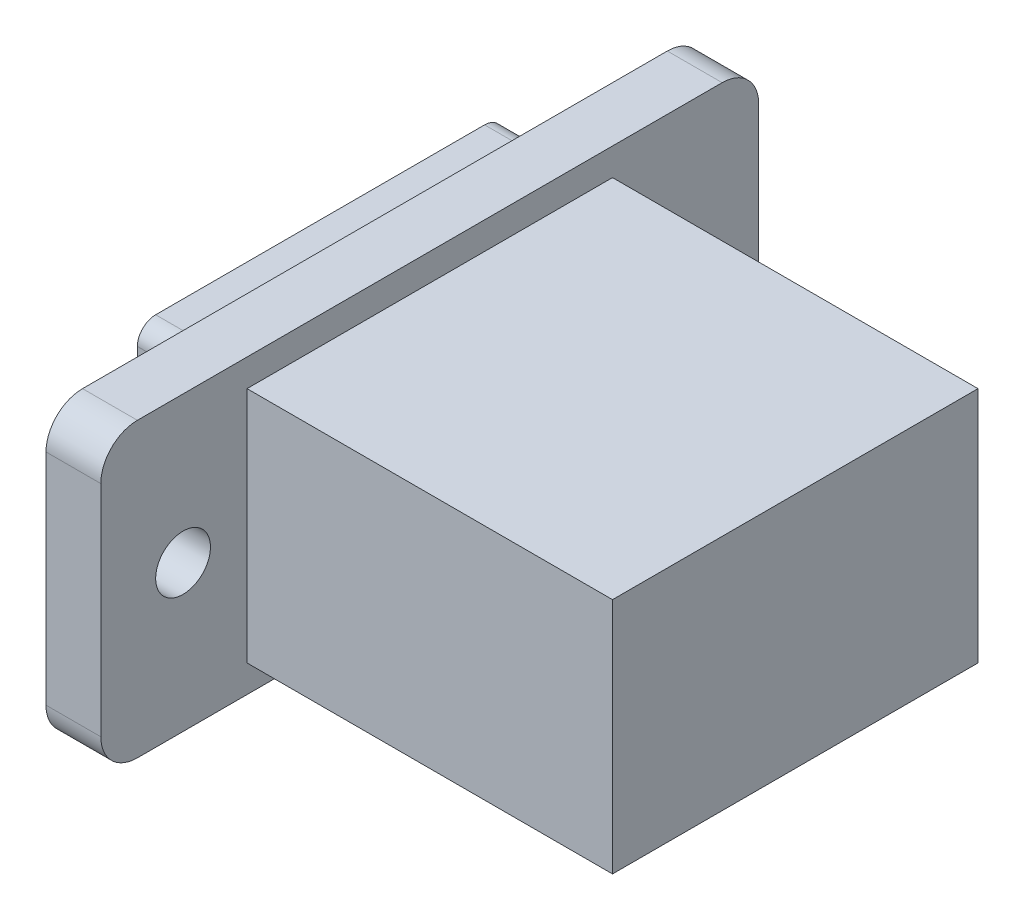
SolidWorks part; units mm, degrees
ref_plane "前视基准面" through (0, 0, 0) normal (0, 0, 1) x (1, 0, 0)
ref_plane "上视基准面" through (0, 0, 0) normal (0, 1, 0) x (1, 0, 0)
ref_plane "右视基准面" through (0, 0, 0) normal (1, 0, 0) x (0, 0, -1)
other "Configuration Table"
sketch "草图1" plane through (0, 0, 0) normal (1, 0, 0) x (0, 0, -1)
  line L1 (0, 0) -> (36, 0)
  line L2 (0, 0) -> (0, 16)
  line L3 (0, 16) -> (36, 16)
  line L4 (36, 0) -> (36, 16)
  dimension "D1" = 16
  dimension "D2" = 36
extrude "凸台-拉伸1" add sketch "草图1" along normal blind 3
sketch "草图2" plane through (0, 0, 0) normal (-1, 0, 0) x (0, 0, 1)
  line L0 (-18, 16) -> (-18, -5.1403) construction
  line L1 (-28, 14.5) -> (-8, 14.5)
  line L2 (-28, 14.5) -> (-28, 1.5)
  line L3 (-28, 1.5) -> (-8, 1.5)
  line L4 (-8, 14.5) -> (-8, 1.5)
  line L5 (-36, 16) -> (0, 16) construction
  line L6 (-36, 8) -> (2.9488, 8) construction
  line L7 (-36, 0) -> (-36, 16) construction
  dimension "D1" = 20
  dimension "D2" = 13
extrude "凸台-拉伸2" add sketch "草图2" along normal blind 3
sketch "草图3" plane through (3, 0, 0) normal (1, 0, 0) x (0, 0, -1)
  line L0 (28, 1.5) -> (8, 1.5) construction
  line L1 (28, 14.5) -> (28, 1.5) construction
  line L2 (8, 14.5) -> (28, 14.5) construction
  line L3 (8, 1.5) -> (8, 14.5) construction
  line L4 (28, 1.5) -> (8, 1.5)
  line L5 (28, 14.5) -> (28, 1.5)
  line L6 (8, 14.5) -> (28, 14.5)
  line L7 (8, 1.5) -> (8, 14.5)
extrude "凸台-拉伸3" add sketch "草图3" along normal blind 20
fillet "圆角1" radius 2 4 edges at (1.5, 0, -36) (1.5, 16, -36) (1.5, 0, 0) (1.5, 16, 0)
fillet "圆角2" radius 1 4 edges at (-1.5, 1.5, -28) (-1.5, 14.5, -28) (-1.5, 1.5, -8) (-1.5, 14.5, -8)
sketch "草图4" plane through (0, 0, 0) normal (-1, 0, 0) x (0, 0, 1)
  line L0 (-36, 8) -> (4.7946, 8) construction
  line L1 (-36, 2) -> (-36, 14) construction
  line L2 (-18, 16) -> (-18, -4.4719) construction
  line L3 (-34, 16) -> (-2, 16) construction
  circle A0 centre (-31.5, 8) radius 1.5
  circle A1 centre (-4.5, 8) radius 1.5
  dimension "D1" = 3
  dimension "D2" = 27
extrude "切除-拉伸1" cut sketch "草图4" against normal through all
